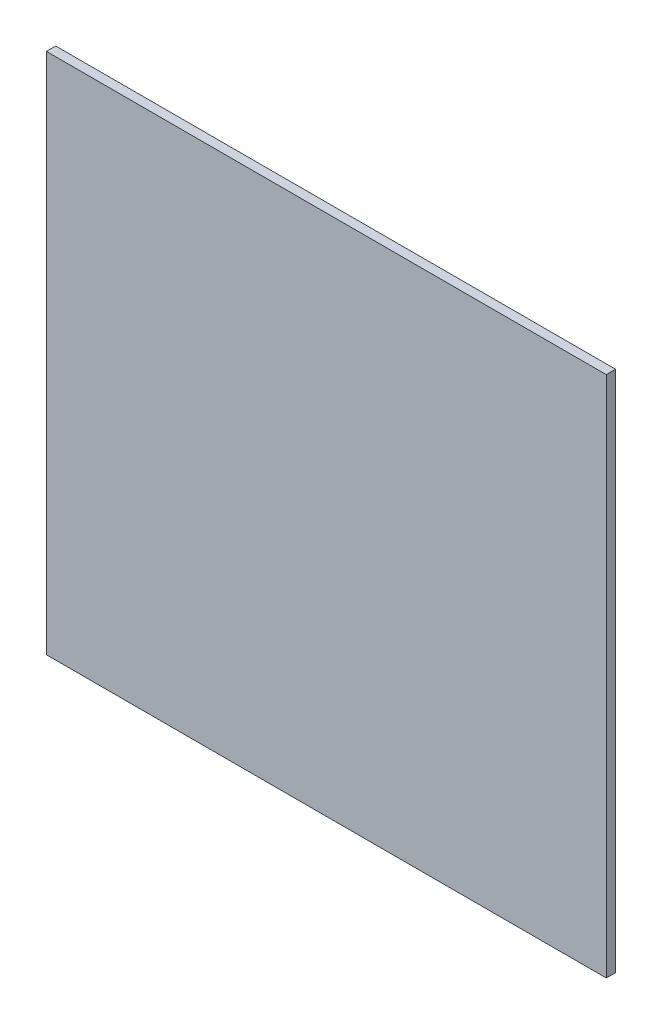
SolidWorks part; units mm, degrees
ref_plane "Ebene vorne" through (0, 0, 0) normal (0, 0, 1) x (1, 0, 0)
ref_plane "Ebene oben" through (0, 0, 0) normal (0, 1, 0) x (1, 0, 0)
ref_plane "Ebene rechts" through (0, 0, 0) normal (1, 0, 0) x (0, 0, -1)
sketch "Skizze1" plane through (0, 0, 0) normal (0, 0, 1) x (1, 0, 0)
  line L1 (-150, 140) -> (150, 140)
  line L2 (-150, 140) -> (-150, -140)
  line L3 (-150, -140) -> (150, -140)
  line L4 (150, 140) -> (150, -140)
  line L5 (-150, 140) -> (150, -140) construction
  line L6 (-150, -140) -> (150, 140) construction
  point P0 (0, 0)
  dimension "D1" = 280
  dimension "D2" = 300
extrude "Aufsatz-Linear austragen1" add sketch "Skizze1" along normal blind 5
